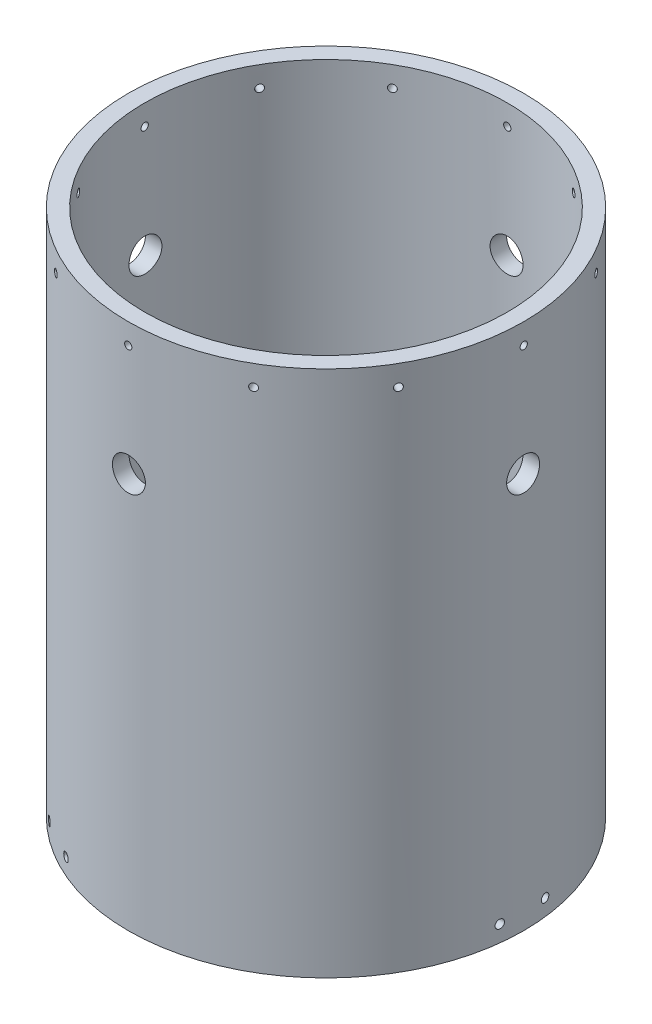
SolidWorks part; units mm, degrees
ref_plane "Front Plane" through (0, 0, 0) normal (0, 0, 1) x (1, 0, 0)
ref_plane "Top Plane" through (0, 0, 0) normal (0, 1, 0) x (1, 0, 0)
ref_plane "Right Plane" through (0, 0, 0) normal (1, 0, 0) x (0, 0, -1)
sketch "Sketch1" plane through (0, 0, 0) normal (0, 1, 0) x (1, 0, 0)
  circle A0 centre (0, 0) radius 139.7
  circle A1 centre (0, 0) radius 152.4
  dimension "D1" = 279.4
  dimension "D2" = 304.8
extrude "Boss-Extrude1" add sketch "Sketch1" along normal blind 406.4
ref_plane "Plane1" through (152.4, 0, 0) normal (1, 0, 0) x (0, 0, -1)
hole_wizard "#10 Clearance Hole1" positions "Sketch2" profile "Sketch3" hole size "#10" standard "ANSI Inch"
sketch "Sketch2" plane through (152.4, 0, 0) normal (1, 0, 0) x (0, 0, -1)
  line L0 (0, 390.525) -> (0, 0)
  line L2 (152.4, 406.4) -> (-152.4, 406.4) construction
  point P0 (0, 390.525)
  dimension "D1" = 15.875
sketch "Sketch3" plane through (152.4, 390.525, 0) normal (0, 1, 0) x (0, 0, -1)
  line L0 (0, 0) -> (0, 343.2351)
  line L1 (0, 343.2351) -> (2.8067, 343.2351)
  line L2 (2.8067, 343.2351) -> (2.8067, 0)
  line L5 (2.8067, 0) -> (0, 0)
  line L11 (0, -6.35) -> (0, 107.95) construction
  dimension "Thru Hole Dia." = 5.6134
  dimension "Thru Hole Depth" = 343.2351
pattern_circular "CirPattern1" count 12 over 360 about axis through (0, 406.4, 0) along (0, 1, 0) of "#10 Clearance Hole1"
ref_plane "Plane2" through (0, 203.2, 0) normal (0, 1, 0) x (1, 0, 0)
sketch "Sketch4" plane through (152.4, 0, 0) normal (1, 0, 0) x (0, 0, -1)
  line L0 (152.4, 406.4) -> (-152.4, 406.4) construction
  circle A0 centre (0, 304.8) radius 12.7
  dimension "D1" = 25.4
  dimension "D2" = 101.6
extrude "Cut-Extrude1" cut sketch "Sketch4" against normal up to next
pattern_circular "CirPattern2" count 4 over 360 about axis through (0, 406.4, 0) along (0, -1, 0) of "Cut-Extrude1"
hole_wizard "Tap Drill for 5/16-18 Tap1" positions "Sketch6" profile "Sketch7" hole size "5/16-18" standard "ANSI Inch"
sketch "Sketch6" plane through (152.4, 0, 0) normal (1, 0, 0) x (0, 0, -1)
  line L0 (-152.4, 0) -> (152.4, 0) construction
  point P0 (17.4625, 12.7)
  point P2 (-17.4625, 12.7)
  dimension "D1" = 12.7
  dimension "D2" = 12.7
  dimension "D3" = 17.4625
  dimension "D4" = 17.4625
sketch "Sketch7" plane through (152.4, 12.7, -17.4625) normal (0, 1, 0) x (0, 0, -1)
  line L0 (0, 0) -> (0, 303.7962)
  line L1 (0, 303.7962) -> (3.2639, 303.7962)
  line L2 (3.2639, 303.7962) -> (3.2639, 0)
  line L5 (3.2639, 0) -> (0, 0)
  line L11 (0, -6.35) -> (0, 107.95) construction
  dimension "Thru Hole Dia." = 6.5278
  dimension "Thru Hole Depth" = 303.7962
pattern_circular "CirPattern3" count 3 over 360 about axis through (0, 406.4, 0) along (0, -1, 0) of "Tap Drill for 5/16-18 Tap1"
